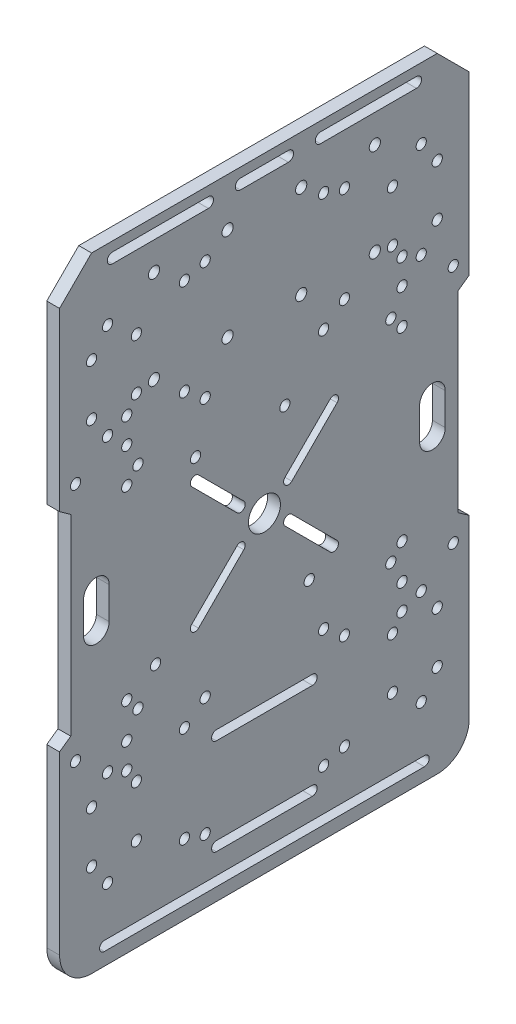
SolidWorks part; units mm, degrees
ref_plane "前视基准面" through (0, 0, 0) normal (0, 0, 1) x (1, 0, 0)
ref_plane "上视基准面" through (0, 0, 0) normal (0, 1, 0) x (1, 0, 0)
ref_plane "右视基准面" through (0, 0, 0) normal (1, 0, 0) x (0, 0, -1)
sketch "草图2" plane through (0, 0, 0) normal (1, 0, 0) x (0, 0, -1)
  line L0 (0, 0) -> (128, 0)
  line L7 (0, 195) -> (128, 195)
  line L8 (64, 0) -> (64, 195) construction
  line L15 (128, 195) -> (128, 0)
  line L18 (0, 195) -> (0, 0)
  dimension "D1" = 128
  dimension "D2" = 195
extrude "凸台-拉伸1" add sketch "草图2" along normal blind 4
sketch "草图3" plane through (4, 0, 0) normal (1, 0, 0) x (0, 0, -1)
  line L0 (0, 97.5) -> (128, 97.5) construction
  line L3 (64, 195) -> (64, 0) construction
  line L4 (128, 195) -> (0, 195) construction
  line L5 (0, 0) -> (128, 0) construction
  line L7 (10, 166) -> (24, 166) construction
  line L8 (10, 166) -> (10, 150) construction
  line L9 (10, 150) -> (24, 150) construction
  line L10 (24, 166) -> (24, 150) construction
  line L11 (128, 0) -> (128, 195) construction
  line L12 (10, 45) -> (24, 45) construction
  line L13 (10, 45) -> (10, 29) construction
  line L14 (10, 29) -> (24, 29) construction
  line L15 (24, 45) -> (24, 29) construction
  line L17 (10, 158) -> (24, 158) construction
  line L18 (0, 195) -> (0, 0) construction
  circle A0 centre (24, 166) radius 1.6
  circle A1 centre (24, 150) radius 1.6
  circle A2 centre (10, 166) radius 1.6
  circle A3 centre (10, 150) radius 1.6
  circle A4 centre (24, 45) radius 1.6
  circle A5 centre (24, 29) radius 1.6
  circle A6 centre (10, 45) radius 1.6
  circle A7 centre (10, 29) radius 1.6
  circle A8 centre (118, 29) radius 1.6
  circle A9 centre (118, 45) radius 1.6
  circle A10 centre (104, 45) radius 1.6
  circle A11 centre (104, 29) radius 1.6
  circle A12 centre (104, 150) radius 1.6
  circle A13 centre (118, 150) radius 1.6
  circle A14 centre (118, 166) radius 1.6
  circle A15 centre (104, 166) radius 1.6
  circle A16 centre (15, 173) radius 1.6
  circle A17 centre (39, 173) radius 1.6
  circle A18 centre (39, 143) radius 1.6
  circle A19 centre (15, 143) radius 1.6
  circle A20 centre (89, 143) radius 1.6
  circle A21 centre (113, 143) radius 1.6
  circle A22 centre (113, 173) radius 1.6
  circle A23 centre (89, 173) radius 1.6
  circle A24 centre (113, 52) radius 1.6
  circle A25 centre (89, 52) radius 1.6
  circle A26 centre (89, 22) radius 1.6
  circle A27 centre (113, 22) radius 1.6
  circle A28 centre (39, 52) radius 1.6
  circle A29 centre (15, 52) radius 1.6
  circle A30 centre (39, 22) radius 1.6
  circle A31 centre (15, 22) radius 1.6
  point P4 (0, 0)
  dimension "D1" = 3.2
  dimension "D6" = 3.2
  dimension "D9" = 3.2
  dimension "D10" = 24
  dimension "D11" = 30
  dimension "D12" = 50
  dimension "D13" = 97.5
  dimension "D2" = 14
  dimension "D3" = 16
  dimension "D4" = 105
  dimension "D5" = 80
  dimension "D7" = 14
  dimension "D8" = 16
extrude "切除-拉伸1" cut sketch "草图3" against normal blind 4
sketch "草图4" plane through (4, 0, 0) normal (1, 0, 0) x (0, 0, -1)
  line L0 (64, 195) -> (64, 0) construction
  line L1 (128, 195) -> (0, 195) construction
  line L2 (0, 0) -> (128, 0) construction
  line L4 (128, 0) -> (128, 195) construction
  line L5 (64, 97.5) -> (128, 97.5) construction
  line L10 (32, 108) -> (96, 108) construction
  line L11 (32, 108) -> (32, 50) construction
  line L12 (32, 50) -> (96, 50) construction
  line L13 (96, 108) -> (96, 50) construction
  line L14 (32, 108) -> (96, 50) construction
  line L15 (32, 50) -> (96, 108) construction
  circle A2 centre (21, 57.5) radius 1.6
  circle A3 centre (21, 49.5) radius 1.6
  circle A4 centre (107, 49.5) radius 1.6
  circle A5 centre (107, 57.5) radius 1.6
  circle A6 centre (21, 145.5) radius 1.6
  circle A7 centre (21, 137.5) radius 1.6
  circle A8 centre (107, 137.5) radius 1.6
  circle A9 centre (107, 145.5) radius 1.6
  point P34 (64, 79)
  point P43 (64, 79)
  dimension "D2" = 3.2
  dimension "D4" = 8
  dimension "D5" = 21
  dimension "D6" = 8
  dimension "D8" = 80
  dimension "D11" = 64
  dimension "D12" = 58
  dimension "D13" = 50
extrude "切除-拉伸2" cut sketch "草图4" against normal blind 4
sketch "草图6" plane through (4, 0, 0) normal (1, 0, 0) x (0, 0, -1)
  line L0 (64, 195) -> (64, 0) construction
  line L1 (128, 195) -> (0, 195) construction
  line L2 (0, 0) -> (128, 0) construction
  line L3 (128, 97.5) -> (0, 97.5) construction
  line L4 (29.5, 180) -> (52.5, 180) construction
  line L5 (29.5, 180) -> (29.5, 151) construction
  line L6 (29.5, 151) -> (52.5, 151) construction
  line L7 (52.5, 180) -> (52.5, 151) construction
  line L8 (45.5, 175) -> (45.5, 138) construction
  line L9 (82.5, 175) -> (82.5, 138) construction
  line L10 (128, 195) -> (0, 195) construction
  line L15 (79, 15) -> (49, 15) construction
  line L16 (79, 13.5) -> (49, 13.5)
  line L17 (79, 16.5) -> (49, 16.5)
  line L18 (79, 45) -> (49, 45) construction
  line L19 (79, 43.5) -> (49, 43.5)
  line L20 (79, 46.5) -> (49, 46.5)
  line L21 (0, 0) -> (128, 0) construction
  line L22 (16.5, 190.4) -> (46.5, 190.4) construction
  line L27 (16.5, 192) -> (46.5, 192)
  line L28 (85.6421, 77.8275) -> (71.5, 91.9697) construction
  line L29 (84.5815, 76.7669) -> (70.4393, 90.909)
  line L30 (86.7028, 78.8882) -> (72.5607, 93.0303)
  line L31 (42.3579, 77.8275) -> (56.5, 91.9697) construction
  line L32 (43.4185, 76.7669) -> (57.5607, 90.909)
  line L33 (41.2972, 78.8882) -> (55.4393, 93.0303)
  line L34 (42.3579, 117.1725) -> (56.5, 103.0303) construction
  line L35 (43.4185, 118.2331) -> (57.5607, 104.091)
  line L36 (41.2972, 116.1118) -> (55.4393, 101.9697)
  line L37 (85.6421, 117.1725) -> (71.5, 103.0303) construction
  line L38 (84.5815, 118.2331) -> (70.4393, 104.091)
  line L39 (86.7028, 116.1118) -> (72.5607, 101.9697)
  line L40 (11.5, 102.5) -> (11.5, 92.5) construction
  line L41 (15.5, 102.5) -> (15.5, 92.5)
  line L42 (7.5, 102.5) -> (7.5, 92.5)
  line L43 (116.5, 102.5) -> (116.5, 92.5) construction
  line L44 (112.5, 102.5) -> (112.5, 92.5)
  line L45 (120.5, 102.5) -> (120.5, 92.5)
  line L46 (0, 195) -> (0, 0) construction
  line L47 (128, 0) -> (128, 195) construction
  line L48 (16.5, 188.8) -> (46.5, 188.8)
  line L49 (56.5, 190.4) -> (71.5, 190.4) construction
  line L50 (56.5, 192) -> (71.5, 192)
  line L51 (56.5, 188.8) -> (71.5, 188.8)
  line L52 (111.5, 190.4) -> (81.5, 190.4) construction
  line L53 (111.5, 192) -> (81.5, 192)
  line L54 (111.5, 188.8) -> (81.5, 188.8)
  line L55 (70.4, 123.5) -> (42.5, 123.5) construction
  line L56 (14, 5.5) -> (114, 5.5) construction
  line L57 (128, 0) -> (128, 195) construction
  line L58 (21, 126.5) -> (107, 126.5) construction
  line L59 (21, 126.5) -> (21, 68.5) construction
  line L60 (21, 68.5) -> (107, 68.5) construction
  line L61 (107, 126.5) -> (107, 68.5) construction
  line L62 (24.5, 130.5) -> (103.5, 130.5) construction
  line L63 (24.5, 130.5) -> (24.5, 64.5) construction
  line L64 (24.5, 64.5) -> (103.5, 64.5) construction
  line L65 (103.5, 130.5) -> (103.5, 64.5) construction
  line L66 (14, 7) -> (114, 7)
  line L67 (14, 4) -> (114, 4)
  line L68 (0, 0) -> (128, 0) construction
  circle A0 centre (52.5, 180) radius 1.75
  circle A1 centre (52.5, 151) radius 1.75
  circle A2 centre (29.5, 151) radius 1.75
  circle A3 centre (29.5, 180) radius 1.75
  circle A4 centre (98.5, 180) radius 1.75
  circle A5 centre (98.5, 151) radius 1.75
  circle A6 centre (75.5, 151) radius 1.75
  circle A7 centre (75.5, 180) radius 1.75
  circle A12 centre (64, 97.5) radius 5
  arc A13 (79, 13.5) -> (79, 16.5) centre (79, 15) ccw
  arc A14 (49, 16.5) -> (49, 13.5) centre (49, 15) ccw
  arc A15 (79, 43.5) -> (79, 46.5) centre (79, 45) ccw
  arc A16 (49, 46.5) -> (49, 43.5) centre (49, 45) ccw
  arc A29 (84.5815, 76.7669) -> (86.7028, 78.8882) centre (85.6421, 77.8275) ccw
  arc A30 (72.5607, 93.0303) -> (70.4393, 90.909) centre (71.5, 91.9697) ccw
  arc A31 (43.4185, 76.7669) -> (41.2972, 78.8882) centre (42.3579, 77.8275) cw
  arc A32 (55.4393, 93.0303) -> (57.5607, 90.909) centre (56.5, 91.9697) cw
  arc A33 (43.4185, 118.2331) -> (41.2972, 116.1118) centre (42.3579, 117.1725) ccw
  arc A34 (55.4393, 101.9697) -> (57.5607, 104.091) centre (56.5, 103.0303) ccw
  arc A35 (84.5815, 118.2331) -> (86.7028, 116.1118) centre (85.6421, 117.1725) cw
  arc A36 (72.5607, 101.9697) -> (70.4393, 104.091) centre (71.5, 103.0303) cw
  arc A37 (15.5, 102.5) -> (7.5, 102.5) centre (11.5, 102.5) ccw
  arc A38 (7.5, 92.5) -> (15.5, 92.5) centre (11.5, 92.5) ccw
  arc A39 (112.5, 102.5) -> (120.5, 102.5) centre (116.5, 102.5) cw
  arc A40 (120.5, 92.5) -> (112.5, 92.5) centre (116.5, 92.5) cw
  circle A41 centre (45.5, 175) radius 1.6
  circle A42 centre (82.5, 175) radius 1.6
  circle A43 centre (82.5, 138) radius 1.6
  circle A44 centre (45.5, 138) radius 1.6
  arc A45 (16.5, 192) -> (16.5, 188.8) centre (16.5, 190.4) ccw
  arc A46 (46.5, 188.8) -> (46.5, 192) centre (46.5, 190.4) ccw
  arc A47 (56.5, 192) -> (56.5, 188.8) centre (56.5, 190.4) ccw
  arc A48 (71.5, 188.8) -> (71.5, 192) centre (71.5, 190.4) ccw
  arc A49 (111.5, 192) -> (111.5, 188.8) centre (111.5, 190.4) cw
  arc A50 (81.5, 188.8) -> (81.5, 192) centre (81.5, 190.4) cw
  circle A51 centre (82.5, 20) radius 1.6
  circle A52 centre (45.5, 20) radius 1.6
  circle A53 centre (45.5, 57) radius 1.6
  circle A54 centre (82.5, 57) radius 1.6
  circle A56 centre (78, 72.5) radius 1.6
  circle A58 centre (42.5, 123.5) radius 1.6
  circle A59 centre (30, 73.7) radius 1.6
  circle A60 centre (70.4, 123.5) radius 1.6
  circle A61 centre (21, 126.5) radius 1.6
  circle A62 centre (107, 126.5) radius 1.6
  circle A63 centre (107, 68.5) radius 1.6
  circle A64 centre (21, 68.5) radius 1.6
  circle A65 centre (24.5, 64.5) radius 1.6
  circle A66 centre (103.5, 64.5) radius 1.6
  circle A67 centre (103.5, 130.5) radius 1.6
  circle A68 centre (24.5, 130.5) radius 1.6
  arc A69 (14, 7) -> (14, 4) centre (14, 5.5) ccw
  arc A70 (114, 4) -> (114, 7) centre (114, 5.5) ccw
  point P42 (64, 15)
  point P49 (64, 45)
  point P56 (31.5, 190.4)
  point P62 (64, 190.4)
  point P71 (96.5, 190.4)
  point P82 (78.5711, 84.8986)
  point P89 (49.4289, 84.8986)
  point P96 (49.4289, 110.1014)
  point P103 (78.5711, 110.1014)
  point P110 (11.5, 97.5)
  point P122 (116.5, 97.5)
  point P155 (64, 5.5)
  dimension "D3" = 3.5
  dimension "D4" = 23
  dimension "D5" = 15
  dimension "D6" = 37
  dimension "D10" = 10
  dimension "D17" = 20
  dimension "D7" = 3.2
  dimension "D32" = 1.2
  dimension "D33" = 51
  dimension "D34" = 7.6
  dimension "D36" = 3.2
  dimension "D37" = 27.9
  dimension "D38" = 50
  dimension "D35" = 25
  dimension "D42" = 3.2
  dimension "D45" = 3.2
  dimension "D1" = 23
  dimension "D2" = 29
  dimension "D8" = 37
  dimension "D9" = 37
  dimension "D11" = 3
  dimension "D12" = 30
  dimension "D13" = 3
  dimension "D14" = 30
  dimension "D15" = 30
  dimension "D16" = 15
  dimension "D18" = 3.2
  dimension "D19" = 3.2
  dimension "D20" = 15
  dimension "D21" = 3
  dimension "D22" = 20
  dimension "D23" = 10
  dimension "D24" = 8
  dimension "D25" = 10
  dimension "D26" = 105
  dimension "D27" = 3
  dimension "D28" = 65
  dimension "D29" = 30
  dimension "D30" = 45
  dimension "D31" = 15
  dimension "D39" = 48
  dimension "D40" = 86
  dimension "D41" = 58
  dimension "D43" = 79
  dimension "D44" = 66
  dimension "D46" = 3
  dimension "D47" = 100
  dimension "D48" = 4
extrude "切除-拉伸4" cut sketch "草图6" against normal blind 10
sketch "草图7" plane through (4, 0, 0) normal (1, 0, 0) x (0, 0, -1)
  line L0 (0, 97.5) -> (128, 97.5) construction
  line L1 (0, 195) -> (0, 0) construction
  line L2 (128, 0) -> (128, 195) construction
  line L3 (64, 0) -> (64, 195) construction
  line L4 (5, 135) -> (123, 135) construction
  line L5 (5, 135) -> (5, 60) construction
  line L6 (5, 60) -> (123, 60) construction
  line L7 (123, 135) -> (123, 60) construction
  line L8 (0, 0) -> (128, 0) construction
  line L9 (128, 195) -> (0, 195) construction
  circle A0 centre (123, 135) radius 1.6
  circle A1 centre (123, 60) radius 1.6
  circle A2 centre (5, 60) radius 1.6
  circle A3 centre (5, 135) radius 1.6
  dimension "D2" = 3.2
  dimension "D1" = 118
  dimension "D3" = 75
extrude "切除-拉伸5" cut sketch "草图7" against normal blind 10
chamfer "倒角1" distance 10 angle 45 2 edges at (2, 195, 0) (2, 195, -128)
fillet "圆角1" radius 10 2 edges at (2, 0, 0) (2, 0, -128)
sketch "草图8" plane through (4, 0, 0) normal (1, 0, 0) x (0, 0, -1)
  line L0 (0, 97.5) -> (128, 97.5) construction
  line L1 (0, 185) -> (0, 10) construction
  line L2 (128, 10) -> (128, 185) construction
  line L3 (128, 130) -> (128, 65)
  line L4 (128, 130) -> (124.5, 127.5)
  line L5 (124.5, 127.5) -> (124.5, 67.5)
  line L6 (128, 65) -> (124.5, 67.5)
  line L7 (120.5, 92.5) -> (120.5, 102.5) construction
  line L8 (64, 195) -> (64, 97.5) construction
  line L9 (118, 195) -> (10, 195) construction
  line L10 (0, 65) -> (3.5, 67.5)
  line L11 (0, 130) -> (0, 65)
  line L12 (3.5, 127.5) -> (3.5, 67.5)
  line L13 (0, 130) -> (3.5, 127.5)
  dimension "D1" = 4
  dimension "D2" = 60
  dimension "D3" = 65
extrude "切除-拉伸6" cut sketch "草图8" against normal blind 10
